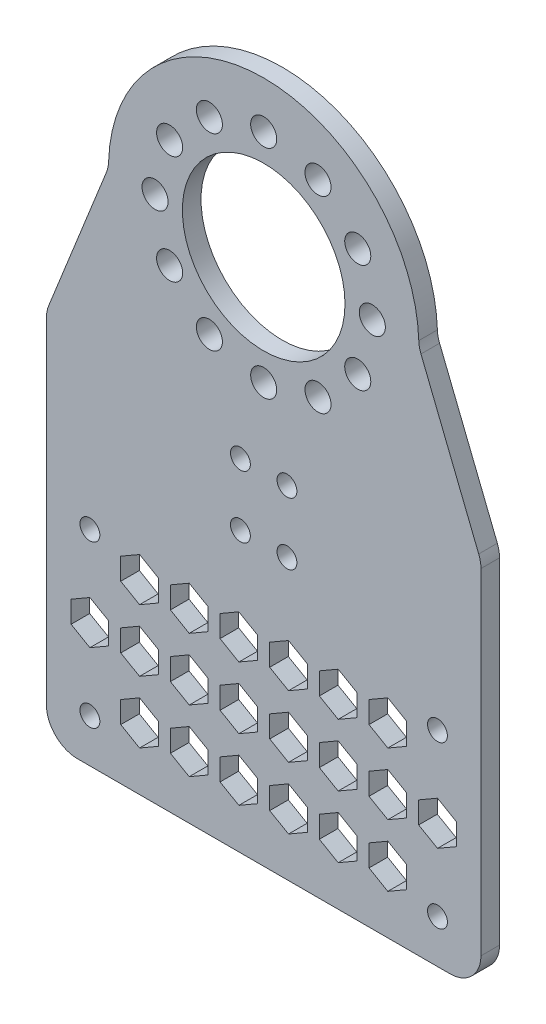
SolidWorks part; units mm, degrees
ref_plane "前视基准面" through (0, 0, 0) normal (0, 0, 1) x (1, 0, 0)
ref_plane "上视基准面" through (0, 0, 0) normal (0, 1, 0) x (1, 0, 0)
ref_plane "右视基准面" through (0, 0, 0) normal (1, 0, 0) x (0, 0, -1)
other "Configuration Table"
sketch "草图1" plane through (0, 0, 0) normal (0, 0, 1) x (1, 0, 0)
  line L0 (-35, 0) -> (-35, -60)
  line L6 (35, -60) -> (35, 0)
  line L7 (0, 0) -> (-35, 0) construction
  line L8 (-25, 25) -> (0, 0) construction
  line L9 (0, 0) -> (25, 25) construction
  line L10 (0, 25) -> (0, 0) construction
  line L11 (-25, 25) -> (-35, 0)
  line L12 (25, 25) -> (35, 0)
  line L13 (-35, -60) -> (-20, -60)
  line L15 (-20, -60) -> (20, -60)
  line L17 (20, -60) -> (35, -60)
  line L18 (-35, -10) -> (35, -10) construction
  line L23 (0, 0) -> (0, -10) construction
  line L25 (-28, -36.5) -> (-28, -27) construction
  line L26 (-24.9689, -38.25) -> (-28, -36.5)
  line L27 (-28, -36.5) -> (-31.0311, -38.25)
  line L28 (-31.0311, -38.25) -> (-31.0311, -41.75)
  line L29 (-31.0311, -41.75) -> (-28, -43.5)
  line L30 (-28, -43.5) -> (-24.9689, -41.75)
  line L31 (-24.9689, -41.75) -> (-24.9689, -38.25)
  line L32 (-16.9689, -38.25) -> (-20, -36.5)
  line L33 (-20, -36.5) -> (-23.0311, -38.25)
  line L34 (-23.0311, -38.25) -> (-23.0311, -41.75)
  line L35 (-23.0311, -41.75) -> (-20, -43.5)
  line L36 (-20, -43.5) -> (-16.9689, -41.75)
  line L37 (-16.9689, -41.75) -> (-16.9689, -38.25)
  line L38 (-8.9689, -38.25) -> (-12, -36.5)
  line L39 (-12, -36.5) -> (-15.0311, -38.25)
  line L40 (-15.0311, -38.25) -> (-15.0311, -41.75)
  line L41 (-15.0311, -41.75) -> (-12, -43.5)
  line L42 (-12, -43.5) -> (-8.9689, -41.75)
  line L43 (-8.9689, -41.75) -> (-8.9689, -38.25)
  line L44 (-0.9689, -38.25) -> (-4, -36.5)
  line L45 (-4, -36.5) -> (-7.0311, -38.25)
  line L46 (-7.0311, -38.25) -> (-7.0311, -41.75)
  line L47 (-7.0311, -41.75) -> (-4, -43.5)
  line L48 (-4, -43.5) -> (-0.9689, -41.75)
  line L49 (-0.9689, -41.75) -> (-0.9689, -38.25)
  line L50 (7.0311, -38.25) -> (4, -36.5)
  line L51 (4, -36.5) -> (0.9689, -38.25)
  line L52 (0.9689, -38.25) -> (0.9689, -41.75)
  line L53 (0.9689, -41.75) -> (4, -43.5)
  line L54 (4, -43.5) -> (7.0311, -41.75)
  line L55 (7.0311, -41.75) -> (7.0311, -38.25)
  line L56 (15.0311, -38.25) -> (12, -36.5)
  line L57 (12, -36.5) -> (8.9689, -38.25)
  line L58 (8.9689, -38.25) -> (8.9689, -41.75)
  line L59 (8.9689, -41.75) -> (12, -43.5)
  line L60 (12, -43.5) -> (15.0311, -41.75)
  line L61 (15.0311, -41.75) -> (15.0311, -38.25)
  line L62 (23.0311, -38.25) -> (20, -36.5)
  line L63 (20, -36.5) -> (16.9689, -38.25)
  line L64 (16.9689, -38.25) -> (16.9689, -41.75)
  line L65 (16.9689, -41.75) -> (20, -43.5)
  line L66 (20, -43.5) -> (23.0311, -41.75)
  line L67 (23.0311, -41.75) -> (23.0311, -38.25)
  line L68 (31.0311, -38.25) -> (28, -36.5)
  line L69 (28, -36.5) -> (24.9689, -38.25)
  line L70 (24.9689, -38.25) -> (24.9689, -41.75)
  line L71 (24.9689, -41.75) -> (28, -43.5)
  line L72 (28, -43.5) -> (31.0311, -41.75)
  line L73 (31.0311, -41.75) -> (31.0311, -38.25)
  line L74 (-16.9689, -48.25) -> (-20, -46.5)
  line L75 (-20, -46.5) -> (-23.0311, -48.25)
  line L76 (-23.0311, -48.25) -> (-23.0311, -51.75)
  line L77 (-23.0311, -51.75) -> (-20, -53.5)
  line L78 (-20, -53.5) -> (-16.9689, -51.75)
  line L79 (-16.9689, -51.75) -> (-16.9689, -48.25)
  line L80 (23.0311, -48.25) -> (20, -46.5)
  line L81 (20, -46.5) -> (16.9689, -48.25)
  line L82 (16.9689, -48.25) -> (16.9689, -51.75)
  line L83 (16.9689, -51.75) -> (20, -53.5)
  line L84 (20, -53.5) -> (23.0311, -51.75)
  line L85 (23.0311, -51.75) -> (23.0311, -48.25)
  line L86 (-0.9689, -48.25) -> (-4, -46.5)
  line L87 (-4, -46.5) -> (-7.0311, -48.25)
  line L88 (-7.0311, -48.25) -> (-7.0311, -51.75)
  line L89 (-7.0311, -51.75) -> (-4, -53.5)
  line L90 (-4, -53.5) -> (-0.9689, -51.75)
  line L91 (-0.9689, -51.75) -> (-0.9689, -48.25)
  line L92 (-8.9689, -48.25) -> (-12, -46.5)
  line L93 (-12, -46.5) -> (-15.0311, -48.25)
  line L94 (-15.0311, -48.25) -> (-15.0311, -51.75)
  line L95 (-15.0311, -51.75) -> (-12, -53.5)
  line L96 (-12, -53.5) -> (-8.9689, -51.75)
  line L97 (-8.9689, -51.75) -> (-8.9689, -48.25)
  line L98 (7.0311, -48.25) -> (4, -46.5)
  line L99 (4, -46.5) -> (0.9689, -48.25)
  line L100 (0.9689, -48.25) -> (0.9689, -51.75)
  line L101 (0.9689, -51.75) -> (4, -53.5)
  line L102 (4, -53.5) -> (7.0311, -51.75)
  line L103 (7.0311, -51.75) -> (7.0311, -48.25)
  line L104 (15.0311, -48.25) -> (12, -46.5)
  line L105 (12, -46.5) -> (8.9689, -48.25)
  line L106 (8.9689, -48.25) -> (8.9689, -51.75)
  line L107 (8.9689, -51.75) -> (12, -53.5)
  line L108 (12, -53.5) -> (15.0311, -51.75)
  line L109 (15.0311, -51.75) -> (15.0311, -48.25)
  line L110 (-16.9689, -28.25) -> (-20, -26.5)
  line L111 (-20, -26.5) -> (-23.0311, -28.25)
  line L112 (-23.0311, -28.25) -> (-23.0311, -31.75)
  line L113 (-23.0311, -31.75) -> (-20, -33.5)
  line L114 (-20, -33.5) -> (-16.9689, -31.75)
  line L115 (-16.9689, -31.75) -> (-16.9689, -28.25)
  line L116 (-8.9689, -28.25) -> (-12, -26.5)
  line L117 (-12, -26.5) -> (-15.0311, -28.25)
  line L118 (-15.0311, -28.25) -> (-15.0311, -31.75)
  line L119 (-15.0311, -31.75) -> (-12, -33.5)
  line L120 (-12, -33.5) -> (-8.9689, -31.75)
  line L121 (-8.9689, -31.75) -> (-8.9689, -28.25)
  line L122 (-0.9689, -28.25) -> (-4, -26.5)
  line L123 (-4, -26.5) -> (-7.0311, -28.25)
  line L124 (-7.0311, -28.25) -> (-7.0311, -31.75)
  line L125 (-7.0311, -31.75) -> (-4, -33.5)
  line L126 (-4, -33.5) -> (-0.9689, -31.75)
  line L127 (-0.9689, -31.75) -> (-0.9689, -28.25)
  line L128 (7.0311, -28.25) -> (4, -26.5)
  line L129 (4, -26.5) -> (0.9689, -28.25)
  line L130 (0.9689, -28.25) -> (0.9689, -31.75)
  line L131 (0.9689, -31.75) -> (4, -33.5)
  line L132 (4, -33.5) -> (7.0311, -31.75)
  line L133 (7.0311, -31.75) -> (7.0311, -28.25)
  line L134 (15.0311, -28.25) -> (12, -26.5)
  line L135 (12, -26.5) -> (8.9689, -28.25)
  line L136 (8.9689, -28.25) -> (8.9689, -31.75)
  line L137 (8.9689, -31.75) -> (12, -33.5)
  line L138 (12, -33.5) -> (15.0311, -31.75)
  line L139 (15.0311, -31.75) -> (15.0311, -28.25)
  line L140 (23.0311, -28.25) -> (20, -26.5)
  line L141 (20, -26.5) -> (16.9689, -28.25)
  line L142 (16.9689, -28.25) -> (16.9689, -31.75)
  line L143 (16.9689, -31.75) -> (20, -33.5)
  line L144 (20, -33.5) -> (23.0311, -31.75)
  line L145 (23.0311, -31.75) -> (23.0311, -28.25)
  line L146 (0, 7.5) -> (0, 0) construction
  arc A0 (-25, 25) -> (25, 25) centre (0, 25) cw
  circle A1 centre (0, 25) radius 13.1
  circle A2 centre (0, 25) radius 25 construction
  circle A7 centre (-28, -53) radius 1.6
  circle A8 centre (-28, -27) radius 1.6
  circle A9 centre (28, -27) radius 1.6
  circle A10 centre (28, -53) radius 1.6
  circle A11 centre (-28, -40) radius 3.0311 construction
  circle A12 centre (0, 7.5) radius 2.1
  circle A13 centre (-8.75, 9.8446) radius 2.1
  circle A14 centre (-15.1554, 16.25) radius 2.1
  circle A15 centre (-17.5, 25) radius 2.1
  circle A16 centre (-15.1554, 33.75) radius 2.1
  circle A17 centre (-8.75, 40.1554) radius 2.1
  circle A18 centre (0, 42.5) radius 2.1
  circle A19 centre (8.75, 40.1554) radius 2.1
  circle A20 centre (15.1554, 33.75) radius 2.1
  circle A21 centre (17.5, 25) radius 2.1
  circle A22 centre (15.1554, 16.25) radius 2.1
  circle A23 centre (8.75, 9.8446) radius 2.1
  circle A24 centre (-3.75, -5) radius 1.6
  circle A25 centre (3.75, -5) radius 1.6
  circle A26 centre (3.75, -15) radius 1.6
  circle A27 centre (-3.75, -15) radius 1.6
  point P186 (0, 25)
  dimension "D6" = 25
  dimension "D7" = 26.2
  dimension "D8" = 50
  dimension "D9" = 25
  dimension "D18" = 3.75
  dimension "D21" = 3.2
  dimension "D36" = 4.2
  dimension "D17" = 3.2
  dimension "D1" = 70
  dimension "D2" = 60
  dimension "D3" = 60
  dimension "D4" = 35
  dimension "D5" = 35
  dimension "D10" = 45
  dimension "D11" = 40
  dimension "D12" = 15
  dimension "D13" = 8
  dimension "D14" = 15
  dimension "D15" = 10
  dimension "D16" = 10
  dimension "D19" = 5
  dimension "D22" = 7
  dimension "D23" = 33
  dimension "D24" = 7
  dimension "D25" = 33
  dimension "D26" = 7
  dimension "D27" = 7
  dimension "D28" = 7
  dimension "D29" = 7
  dimension "D30" = 3.5
  dimension "D31" = 13
  dimension "D32" = 7
  dimension "D33" = 8
  dimension "D37" = 17.5
  dimension "D20" = 10
  dimension "D34" = 2
  dimension "D35" = 2
  dimension "D38" = 12
extrude "凸台-拉伸1" add sketch "草图1" along normal blind 3 contours A0 L11 L0 L13 L15 L17 L6 L12 A25 A24 A23 A22 A21 A20 A19 A18 A17 A16 A15 A14 A13 A12 A10 A9 A8 A7 A1 L145 L144 L143 L142
fillet "圆角1" radius 5 6 edges at (-25, 25, 1.5) (25, 25, 1.5) (-35, 0, 1.5) (35, 0, 1.5) (35, -60, 1.5) (-35, -60, 1.5)
